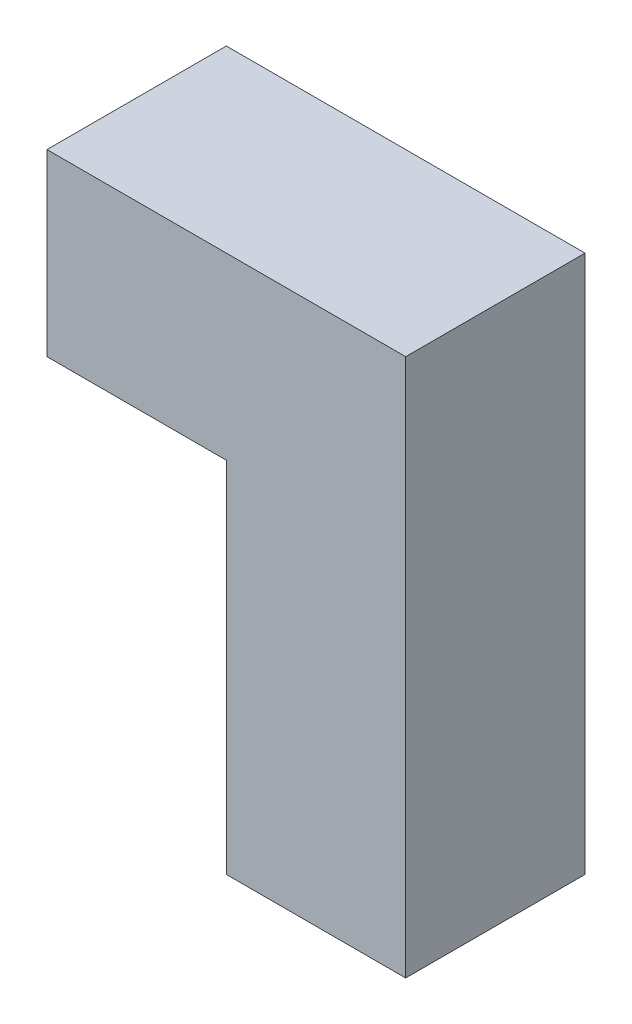
SolidWorks part; units mm, degrees
ref_plane "Front Plane" through (0, 0, 0) normal (0, 0, 1) x (1, 0, 0)
ref_plane "Top Plane" through (0, 0, 0) normal (0, 1, 0) x (1, 0, 0)
ref_plane "Right Plane" through (0, 0, 0) normal (1, 0, 0) x (0, 0, -1)
sketch "Sketch1" plane through (0, 0, 0) normal (0, 0, 1) x (1, 0, 0)
  line L0 (0, 0) -> (0, 19.05)
  line L1 (0, 19.05) -> (38.1, 19.05)
  line L2 (38.1, 19.05) -> (38.1, -38.1)
  line L3 (38.1, -38.1) -> (19.05, -38.1)
  line L4 (19.05, -38.1) -> (19.05, 0)
  line L5 (19.05, 0) -> (0, 0)
  dimension "D1" = 19.05
  dimension "D2" = 57.15
  dimension "D3" = 19.05
  dimension "D4" = 19.05
extrude "Boss-Extrude1" add sketch "Sketch1" along normal blind 19.05 contours L5 L0 L1 L2 L3 L4
